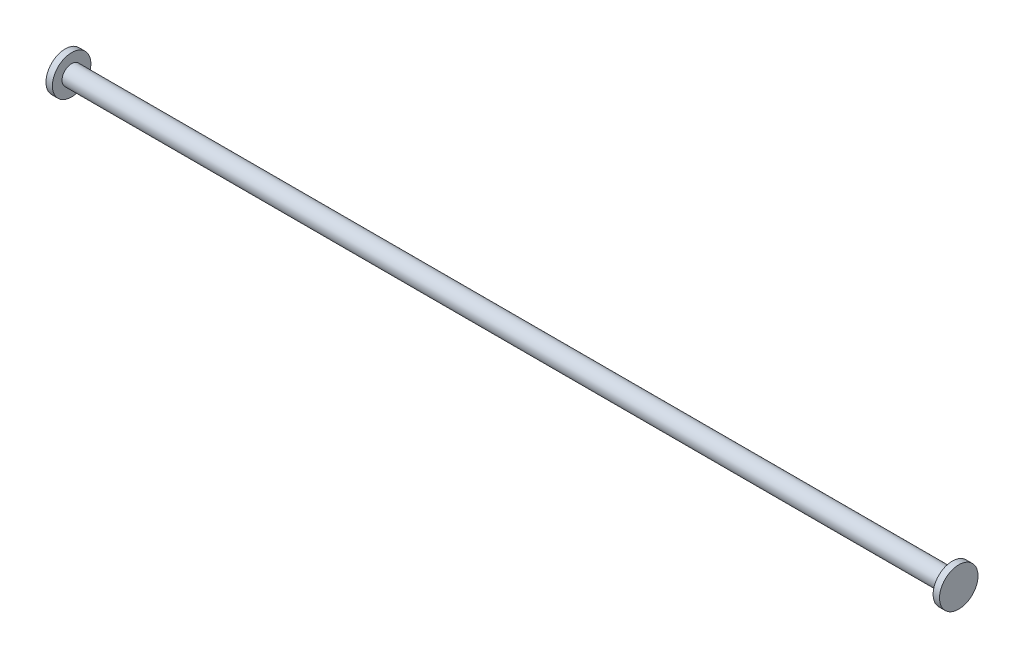
SolidWorks part; units mm, degrees
ref_plane "Front Plane" through (0, 0, 0) normal (0, 0, 1) x (1, 0, 0)
ref_plane "Top Plane" through (0, 0, 0) normal (0, 1, 0) x (1, 0, 0)
ref_plane "Right Plane" through (0, 0, 0) normal (1, 0, 0) x (0, 0, -1)
sketch "Sketch1" plane through (0, 0, 0) normal (1, 0, 0) x (0, 0, -1)
  circle A0 centre (0, 0) radius 38.1
  dimension "D1" = 76.2
extrude "Boss-Extrude1" add sketch "Sketch1" along normal mid plane 3487.293
sketch "Sketch2" plane through (1743.6465, 0, 0) normal (1, 0, 0) x (0, 0, -1)
  circle A0 centre (0, 0) radius 76.2
  dimension "D1" = 152.4
extrude "Boss-Extrude2" add sketch "Sketch2" along normal blind 25.4
mirror "Mirror1" about plane through (0, 0, 0) normal (1, 0, 0) of "Boss-Extrude2"
